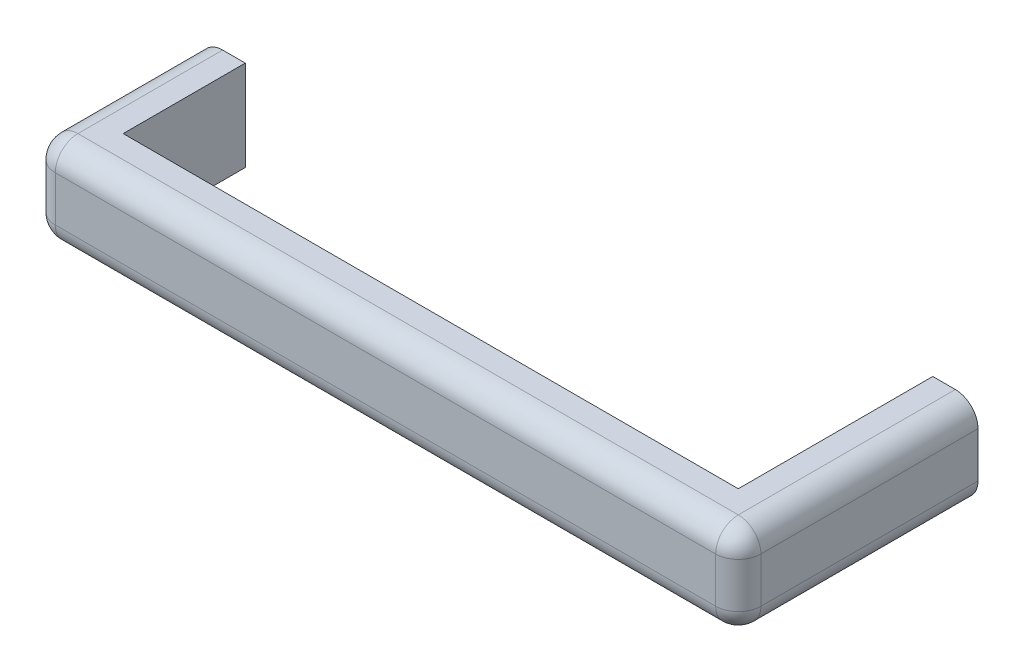
SolidWorks part; units mm, degrees
ref_plane "Front Plane" through (0, 0, 0) normal (0, 0, 1) x (1, 0, 0)
ref_plane "Top Plane" through (0, 0, 0) normal (0, 1, 0) x (1, 0, 0)
ref_plane "Right Plane" through (0, 0, 0) normal (1, 0, 0) x (0, 0, -1)
sketch "Sketch1" plane through (0, 0, 0) normal (0, 1, 0) x (1, 0, 0)
  line L1 (63.5, 63.5) -> (927.1, 63.5)
  line L2 (0, 63.5) -> (0, 0)
  line L3 (0, 0) -> (990.6, 0)
  line L4 (990.6, 63.5) -> (990.6, 0)
  line L6 (990.6, 63.5) -> (990.6, 336.55)
  line L7 (990.6, 336.55) -> (927.1, 336.55)
  line L8 (927.1, 63.5) -> (927.1, 336.55)
  line L10 (0, 63.5) -> (0, 234.95)
  line L11 (0, 234.95) -> (63.5, 234.95)
  line L12 (63.5, 63.5) -> (63.5, 234.95)
  dimension "D1" = 863.6
  dimension "D2" = 171.45
  dimension "D3" = 273.05
  dimension "D4" = 63.5
  dimension "D5" = 63.5
  dimension "D6" = 63.5
extrude "Boss-Extrude1" add sketch "Sketch1" along normal blind 127
fillet "Fillet1" radius 31.75 8 edges at (990.6, 63.5, 0) (0, 63.5, 0) (990.6, 0, -168.275) (0, 0, -117.475) (495.3, 0, 0) (990.6, 127, -168.275) (0, 127, -117.475) (495.3, 127, 0)
